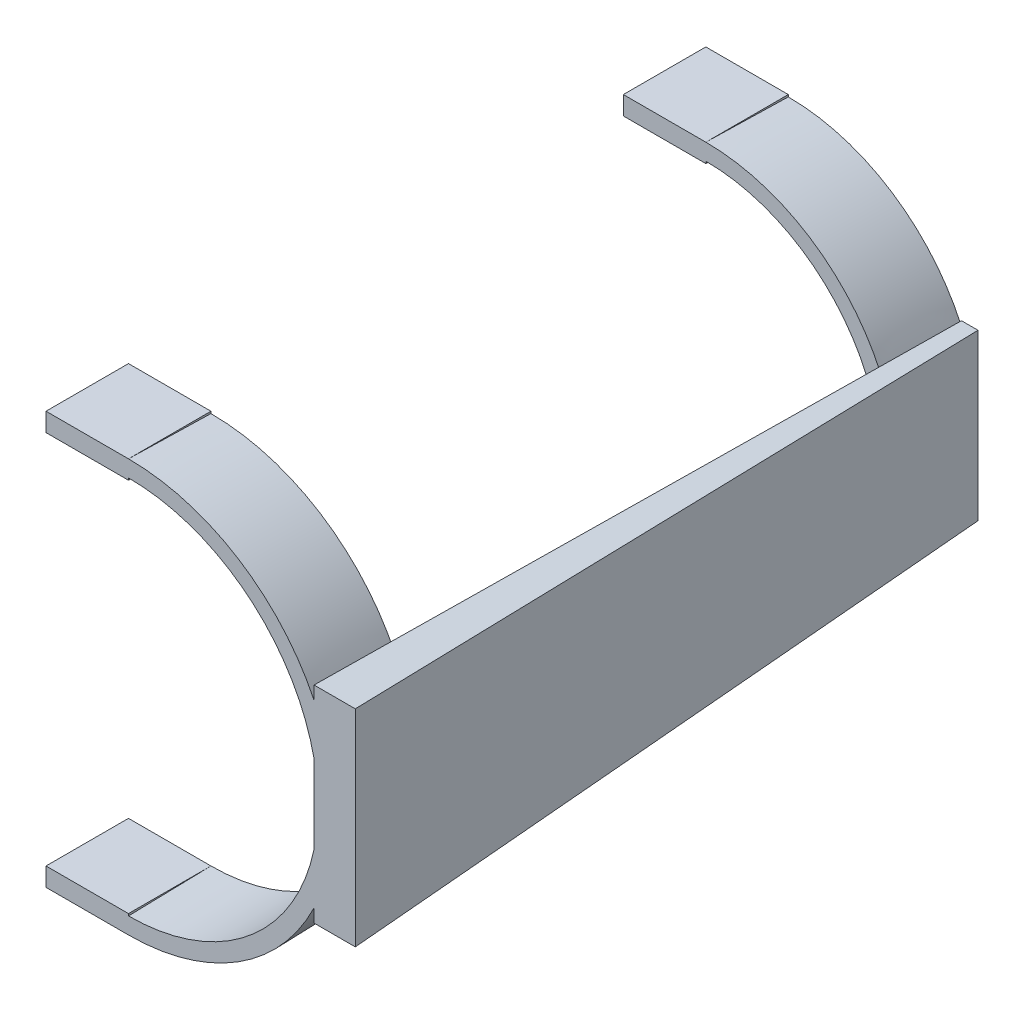
SolidWorks part; units mm, degrees
ref_plane "Front" through (0, 0, 0) normal (0, 0, 1) x (1, 0, 0)
ref_plane "Top" through (0, 0, 0) normal (0, 1, 0) x (1, 0, 0)
ref_plane "Right" through (0, 0, 0) normal (1, 0, 0) x (0, 0, -1)
sketch "草图1" plane through (0, 0, 0) normal (1, 0, 0) x (0, 0, -1)
  line L0 (0, 46) -> (0, 75.0518) construction
  line L1 (0, 0) -> (-171.072, 0) construction
  line L2 (0, 50) -> (0, 46)
  line L3 (160, 42) -> (160, 46)
  line L4 (0, 0) -> (160, 0)
  line L5 (0, 50) -> (160, 46)
  line L6 (0, 46) -> (160, 42)
  point P7 (0, 46)
  point P8 (160, 42)
  dimension "D1" = 50
  dimension "D2" = 160
  dimension "D3" = 46
  dimension "D4" = 46
  dimension "D5" = 42
revolve "旋转1" add sketch "草图1" angle 180 about L4
sketch "草图2" plane through (0, 0, 0) normal (1, 0, 0) x (0, 0, -1)
  line L0 (0, 50) -> (0, -50) construction
  line L1 (160, 46) -> (160, -46) construction
  line L3 (20, 60.115) -> (140, 60.115)
  line L4 (20, 60.115) -> (20, -64.3514)
  line L5 (20, -64.3514) -> (140, -64.3514)
  line L6 (140, 60.115) -> (140, -64.3514)
  dimension "D1" = 20
  dimension "D2" = 20
extrude "切除-拉伸1" cut sketch "草图2" along normal through all
sketch "草图3" plane through (0, 0, 0) normal (0, 0, 1) x (1, 0, 0)
  line L0 (0, 0) -> (53.4175, 0) construction
  line L2 (55, 25) -> (45, 25)
  line L3 (55, 25) -> (55, -25)
  line L4 (55, -25) -> (45, -25)
  line L5 (45, 25) -> (45, -25)
  dimension "D1" = 50
  dimension "D2" = 25
  dimension "D3" = 10
  dimension "D4" = 55
sketch "草图4" plane through (0, 0, -160) normal (0, 0, -1) x (-1, 0, 0)
  line L0 (0, 0) -> (-66.5571, 0) construction
  line L2 (-46, 20) -> (-42, 20)
  line L3 (-46, 20) -> (-46, -20)
  line L4 (-46, -20) -> (-42, -20)
  line L5 (-42, 20) -> (-42, -20)
  dimension "D1" = 46
  dimension "D2" = 4
  dimension "D3" = 40
  dimension "D4" = 20
loft "放样1" add profiles "草图3", "草图4"
sketch "草图6" plane through (0, 0, 0) normal (-1, 0, 0) x (0, 0, 1)
  line L0 (-20, -45.5) -> (-20, -49.5) construction
  line L1 (-20, 45.5) -> (0, 45.5)
  line L2 (-20, 45.5) -> (-20, 50)
  line L3 (-20, 50) -> (0, 50)
  line L4 (0, 45.5) -> (0, 50)
  line L5 (0, -50) -> (-20, -50)
  line L6 (0, -50) -> (0, -45.5)
  line L7 (0, -45.5) -> (-20, -45.5)
  line L8 (-20, -50) -> (-20, -45.5)
  line L9 (0, -46) -> (-20, -45.5) construction
  line L11 (-140, -46.5) -> (-160, -46.5)
  line L12 (-140, -46.5) -> (-140, -42)
  line L13 (-140, -42) -> (-160, -42)
  line L14 (-160, -46.5) -> (-160, -42)
  line L15 (-140, 46.5) -> (-160, 46.5)
  line L16 (-140, 46.5) -> (-140, 42)
  line L17 (-140, 42) -> (-160, 42)
  line L18 (-160, 46.5) -> (-160, 42)
extrude "凸台-拉伸1" add sketch "草图6" along normal blind 20
